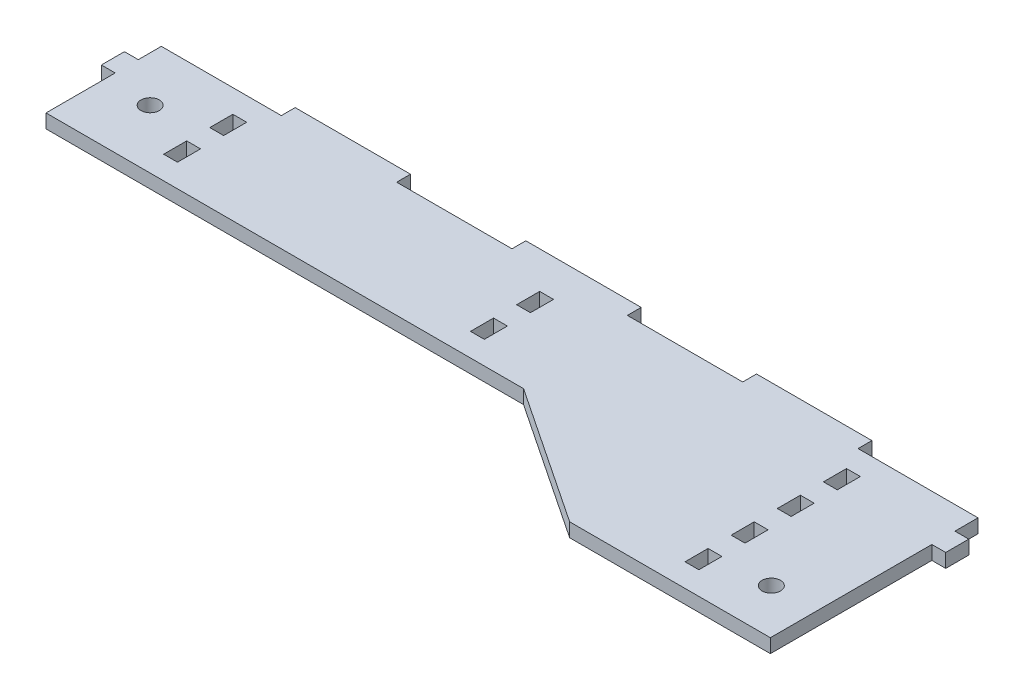
SolidWorks part; units mm, degrees
material "Buk"
ref_plane "Přední rovina" through (0, 0, 0) normal (0, 0, 1) x (1, 0, 0)
ref_plane "Horní rovina" through (0, 0, 0) normal (0, 1, 0) x (1, 0, 0)
ref_plane "Pravá rovina" through (0, 0, 0) normal (1, 0, 0) x (0, 0, -1)
sketch "Skica1" plane through (0, 0, 0) normal (0, 1, 0) x (1, 0, 0)
  line L0 (-88.5, 0) -> (88.5, 0)
  line L1 (88.5, 0) -> (88.5, -45)
  line L2 (88.5, -45) -> (45, -45)
  line L3 (45, -45) -> (15, -25)
  line L4 (15, -25) -> (-88.5, -25)
  line L5 (-88.5, -25) -> (-88.5, 0)
  line L6 (60, 0) -> (60, -45) construction
  dimension "D1" = 177
  dimension "D2" = 25
  dimension "D3" = 45
  dimension "D4" = 60
  dimension "D5" = 15
  dimension "D6" = 15
extrude "Přidat vysunutím1" add sketch "Skica1" along normal blind 3
sketch "Skica2" plane through (0, 0, 0) normal (0, 1, 0) x (1, 0, 0)
  line L0 (88.5, 0) -> (-88.5, 0) construction
  line L1 (-1.5, -5) -> (1.5, -5)
  line L2 (-1.5, -5) -> (-1.5, -10)
  line L3 (-1.5, -10) -> (1.5, -10)
  line L4 (1.5, -5) -> (1.5, -10)
  line L5 (-1.5, -15) -> (1.5, -15)
  line L6 (-1.5, -15) -> (-1.5, -20)
  line L7 (-1.5, -20) -> (1.5, -20)
  line L8 (1.5, -15) -> (1.5, -20)
  line L9 (0, 0) -> (0, -5) construction
  line L10 (65, -20) -> (65, -25) construction
  line L11 (-65, -5) -> (-68, -5)
  line L12 (-65, -5) -> (-65, -10)
  line L13 (-65, -10) -> (-68, -10)
  line L14 (-68, -5) -> (-68, -10)
  line L15 (-65, -15) -> (-68, -15)
  line L16 (-65, -15) -> (-65, -20)
  line L17 (-65, -20) -> (-68, -20)
  line L18 (-68, -15) -> (-68, -20)
  line L19 (68, -10) -> (65, -10)
  line L20 (68, -10) -> (68, -5)
  line L21 (68, -5) -> (65, -5)
  line L22 (65, -10) -> (65, -5)
  line L23 (65, -15) -> (68, -15)
  line L24 (65, -15) -> (65, -20)
  line L25 (65, -20) -> (68, -20)
  line L26 (68, -15) -> (68, -20)
  line L27 (65, -25) -> (68, -25)
  line L28 (65, -25) -> (65, -30)
  line L29 (65, -30) -> (68, -30)
  line L30 (68, -25) -> (68, -30)
  line L31 (65, -35) -> (68, -35)
  line L32 (65, -35) -> (65, -40)
  line L33 (65, -40) -> (68, -40)
  line L34 (68, -35) -> (68, -40)
  line L35 (-65, -40) -> (65, -40) construction
  line L36 (65, -30) -> (65, -35) construction
  line L37 (0, 0) -> (0, -40) construction
  dimension "D1" = 5
  dimension "D2" = 5
  dimension "D3" = 5
  dimension "D4" = 3
  dimension "D5" = 130
extrude "Odebrat vysunutím1" cut sketch "Skica2" along normal through all
sketch "Skica3" plane through (0, 0, 0) normal (0, 1, 0) x (1, 0, 0)
  line L0 (88.5, 0) -> (-88.5, 0) construction
  line L1 (-62.5, 0) -> (-37.5, 0)
  line L2 (-62.5, 0) -> (-62.5, 3)
  line L3 (-62.5, 3) -> (-37.5, 3)
  line L4 (-37.5, 0) -> (-37.5, 3)
  line L5 (-68, -5) -> (-68, -10) construction
  line L6 (-12.5, 0) -> (12.5, 0)
  line L7 (-12.5, 0) -> (-12.5, 3)
  line L8 (-12.5, 3) -> (12.5, 3)
  line L9 (12.5, 0) -> (12.5, 3)
  line L10 (37.5, 0) -> (62.5, 0)
  line L11 (37.5, 0) -> (37.5, 3)
  line L12 (37.5, 3) -> (62.5, 3)
  line L13 (62.5, 0) -> (62.5, 3)
  line L14 (-37.5, 3) -> (-12.5, 3) construction
  line L15 (-12.5, 3) -> (-12.3839, 2.2982) construction
  line L16 (0, 0) -> (0, -35.9142) construction
  line L71 (88.5, -45) -> (88.5, 0) construction
  line L72 (88.5, -5) -> (91.5, -5)
  line L75 (88.5, -5) -> (88.5, -10)
  line L76 (-65, -5) -> (-68, -5) construction
  line L77 (-88.5, 0) -> (-88.5, -25) construction
  line L78 (-88.5, -5) -> (-91.5, -5)
  line L79 (-88.5, -5) -> (-88.5, -10)
  line L80 (-88.5, -10) -> (-91.5, -10)
  line L81 (-91.5, -5) -> (-91.5, -10)
  line L83 (88.5, -10) -> (91.5, -10)
  line L84 (91.5, -5) -> (91.5, -10)
  line L85 (68, -5) -> (65, -5) construction
  line L86 (65, -10) -> (68, -10) construction
  dimension "D1" = 25
  dimension "D2" = 3
extrude "Přidat vysunutím2" add sketch "Skica3" along normal up to surface (3 mm away) up to face at (66.5, 3, 27.5)
sketch "Skica4" plane through (0, 0, 0) normal (0, 1, 0) x (1, 0, 0)
  line L1 (-62.5, 0) -> (-88.5, 0) construction
  line L2 (-85, 33.8325) -> (85, 33.8325) construction
  line L3 (0, 0) -> (0, 33.8325) construction
  circle A0 centre (-78.65, -12.27) radius 2
  circle A1 centre (78.83, -35.13) radius 2
  dimension "D1" = 6.35
  dimension "D3" = 157.48
  dimension "D4" = 4
  dimension "D5" = 22.86
  dimension "D2" = 12.27
  dimension "D6" = 170
extrude "Odebrat vysunutím3" cut sketch "Skica4" along normal through all
